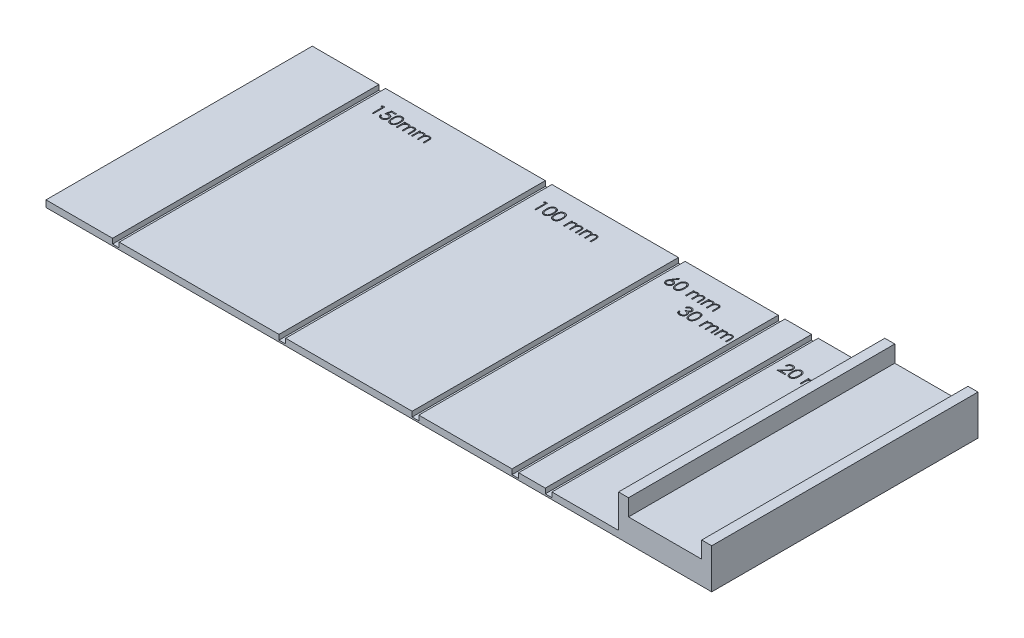
SolidWorks part; units mm, degrees
ref_plane "Front Plane" through (0, 0, 0) normal (0, 0, 1) x (1, 0, 0)
ref_plane "Top Plane" through (0, 0, 0) normal (0, 1, 0) x (1, 0, 0)
ref_plane "Right Plane" through (0, 0, 0) normal (1, 0, 0) x (0, 0, -1)
sketch "Sketch1" plane through (0, 0, 0) normal (0, 1, 0) x (1, 0, 0)
  line L1 (-100, 40) -> (100, 40)
  line L2 (-100, 40) -> (-100, -40)
  line L3 (-100, -40) -> (100, -40)
  line L4 (100, 40) -> (100, -40)
  line L5 (-100, 40) -> (100, -40) construction
  line L6 (-100, -40) -> (100, 40) construction
  point P0 (0, 0)
  dimension "D1" = 80
  dimension "D2" = 200
extrude "Boss-Extrude1" add sketch "Sketch1" along normal blind 2
sketch "Sketch2" plane through (0, 2, 0) normal (0, 1, 0) x (1, 0, 0)
  line L0 (-100, -40) -> (100, -40) construction
  line L1 (100, 40) -> (72, 40)
  line L2 (100, 40) -> (100, -40)
  line L3 (100, -40) -> (72, -40)
  line L4 (72, 40) -> (72, -40)
  dimension "D1" = 28
extrude "Boss-Extrude2" add sketch "Sketch2" along normal blind 10
sketch "Sketch3" plane through (0, 12, 0) normal (0, 1, 0) x (1, 0, 0)
  line L0 (100, 40) -> (72, 40) construction
  line L1 (75, 40) -> (97, 40)
  line L2 (75, 40) -> (75, -40)
  line L3 (75, -40) -> (97, -40)
  line L4 (97, 40) -> (97, -40)
  line L5 (72, -40) -> (100, -40) construction
  point P8 (86, 40)
  point P9 (86, 40)
  dimension "D1" = 22
extrude "Cut-Extrude1" cut sketch "Sketch3" against normal blind 5 contours L2 L3 L4 L1
sketch "Sketch4" plane through (0, 2, 0) normal (0, 1, 0) x (1, 0, 0)
  line L0 (72, 40) -> (-100, 40) construction
  line L1 (50, 40) -> (52, 40)
  line L2 (50, 40) -> (50, -40)
  line L3 (50, -40) -> (52, -40)
  line L4 (52, 40) -> (52, -40)
  line L5 (-100, -40) -> (72, -40) construction
  line L6 (72, 40) -> (72, -40) construction
  line L7 (10, 40) -> (12, 40)
  line L8 (10, 40) -> (10, -40)
  line L9 (10, -40) -> (12, -40)
  line L10 (12, 40) -> (12, -40)
  line L11 (-30, 40) -> (-28, 40)
  line L12 (-30, 40) -> (-30, -40)
  line L13 (-30, -40) -> (-28, -40)
  line L14 (-28, 40) -> (-28, -40)
  line L15 (40, 40) -> (42, 40)
  line L16 (40, 40) -> (40, -40)
  line L17 (40, -40) -> (42, -40)
  line L18 (42, 40) -> (42, -40)
  line L19 (72, 40) -> (72, -40) construction
  line L21 (-80, 40) -> (-78, 40)
  line L22 (-80, 40) -> (-80, -40)
  line L23 (-80, -40) -> (-78, -40)
  line L24 (-78, 40) -> (-78, -40)
  text T0 "150mm"
  text T1 "100 mm"
  text T2 "60 mm"
  text T3 "30 mm"
  text T4 "20 mm\r\n"
  dimension "D1" = 2
  dimension "D2" = 2
  dimension "D3" = 2
  dimension "D4" = 2
  dimension "D5" = 20
  dimension "D6" = 30
  dimension "D7" = 60
  dimension "D8" = 100
  dimension "D9" = 2
  dimension "D10" = 150
extrude "Cut-Extrude2" cut sketch "Sketch4" against normal blind 1.5
